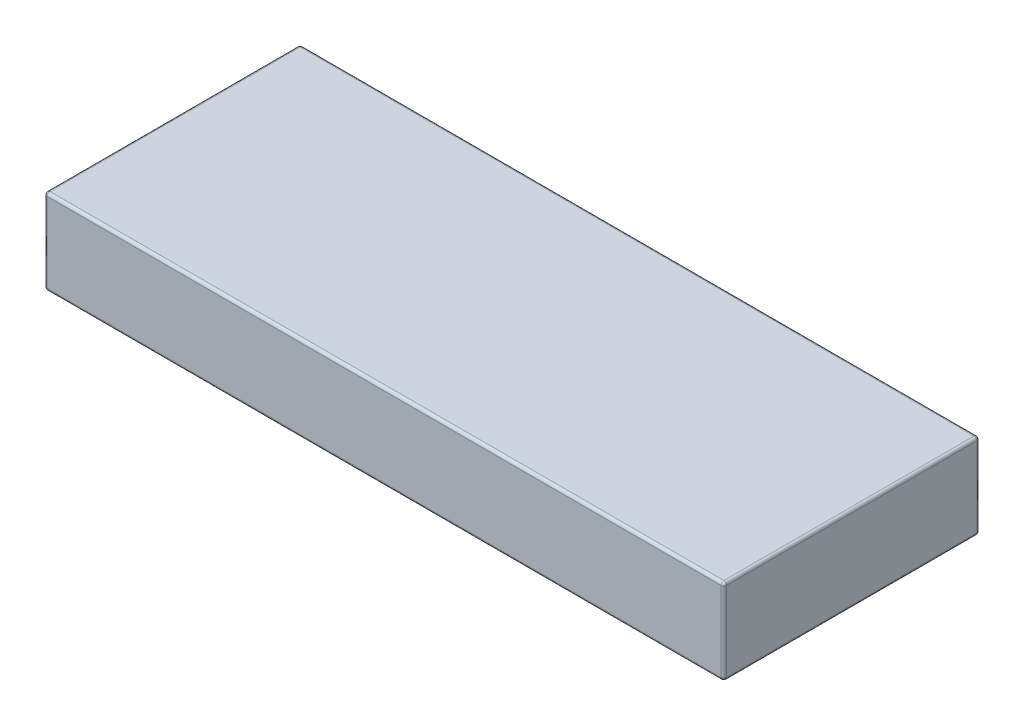
SolidWorks part; units mm, degrees
ref_plane "Front Plane" through (0, 0, 0) normal (0, 0, 1) x (1, 0, 0)
ref_plane "Top Plane" through (0, 0, 0) normal (0, 1, 0) x (1, 0, 0)
ref_plane "Right Plane" through (0, 0, 0) normal (1, 0, 0) x (0, 0, -1)
sketch "Sketch1" plane through (0, 0, 0) normal (0, 1, 0) x (1, 0, 0)
  line L1 (0, 0) -> (30.353, 0)
  line L2 (0, 0) -> (0, 11.43)
  line L3 (0, 11.43) -> (30.353, 11.43)
  line L4 (30.353, 0) -> (30.353, 11.43)
  dimension "D1" = 30.353
  dimension "D2" = 11.43
extrude "Boss-Extrude1" add sketch "Sketch1" along normal blind 3.81
fillet "Fillet1" radius 0.127 12 edges at (0, 0, -5.715) (15.1765, 0, 0) (30.353, 0, -5.715) (15.1765, 0, -11.43) (0, 3.81, -5.715) (15.1765, 3.81, 0) (30.353, 3.81, -5.715) (15.1765, 3.81, -11.43) (0, 1.905, -11.43) (30.353, 1.905, -11.43) (0, 1.905, 0) (30.353, 1.905, 0)
